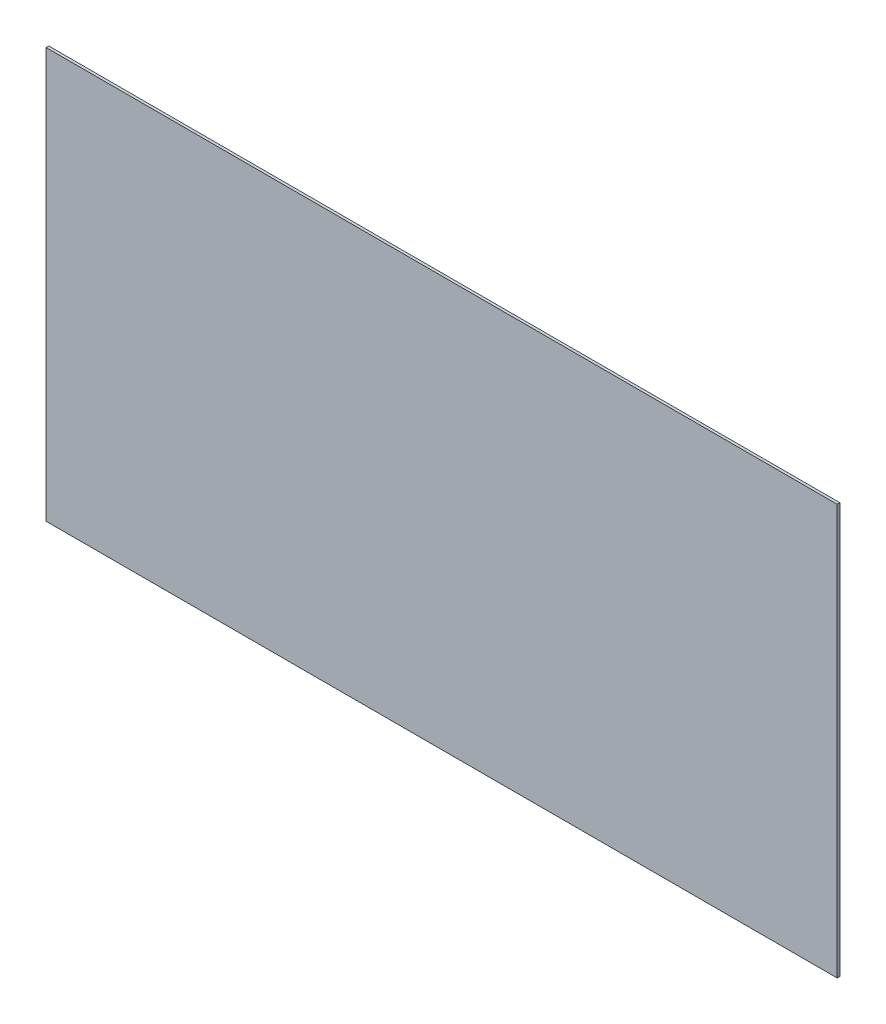
SolidWorks part; units mm, degrees
material "铜"
ref_plane "前视基准面" through (0, 0, 0) normal (0, 0, 1) x (1, 0, 0)
ref_plane "上视基准面" through (0, 0, 0) normal (0, 1, 0) x (1, 0, 0)
ref_plane "右视基准面" through (0, 0, 0) normal (1, 0, 0) x (0, 0, -1)
sketch "草图1" plane through (0, 0, 0) normal (0, 0, 1) x (1, 0, 0)
  line L1 (0, 0) -> (295, 0)
  line L2 (0, 0) -> (0, 153)
  line L3 (0, 153) -> (295, 153)
  line L4 (295, 0) -> (295, 153)
  dimension "D1" = 295
  dimension "D2" = 153
extrude "凸台-拉伸1" add sketch "草图1" along normal blind 1
